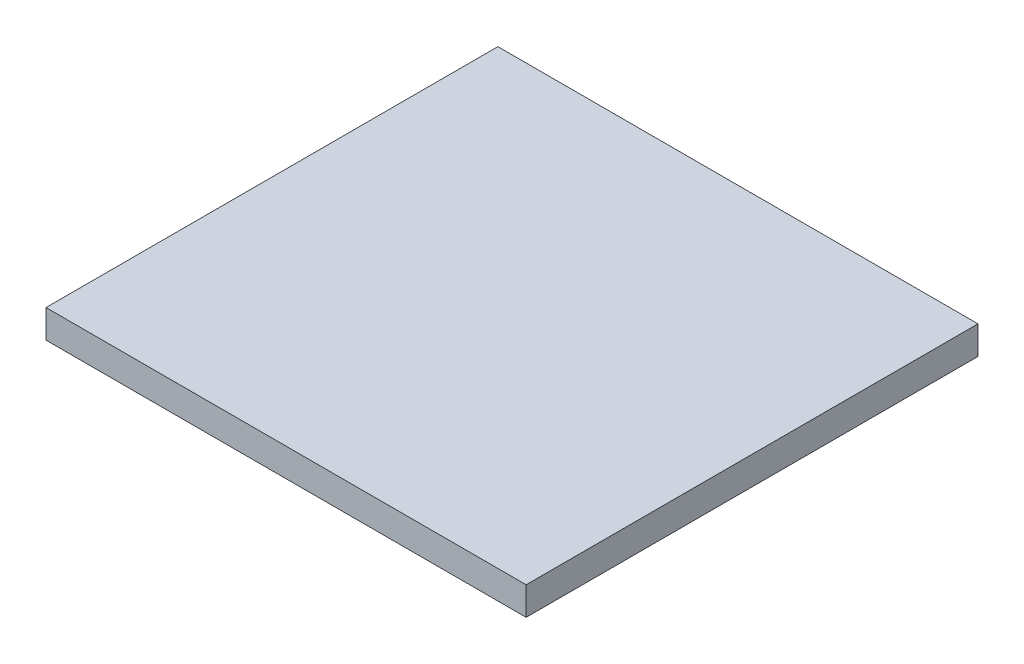
SolidWorks part; units mm, degrees
ref_plane "Front Plane" through (0, 0, 0) normal (0, 0, 1) x (1, 0, 0)
ref_plane "Top Plane" through (0, 0, 0) normal (0, 1, 0) x (1, 0, 0)
ref_plane "Right Plane" through (0, 0, 0) normal (1, 0, 0) x (0, 0, -1)
sketch "Sketch1" plane through (0, 0, 0) normal (0, 1, 0) x (1, 0, 0)
  line L1 (-17, 16) -> (17, 16)
  line L2 (-17, 16) -> (-17, -16)
  line L3 (-17, -16) -> (17, -16)
  line L4 (17, 16) -> (17, -16)
  line L5 (-17, 16) -> (17, -16) construction
  line L6 (-17, -16) -> (17, 16) construction
  point P0 (0, 0)
  dimension "D1" = 34
  dimension "D2" = 32
extrude "Boss-Extrude1" add sketch "Sketch1" along normal blind 2
